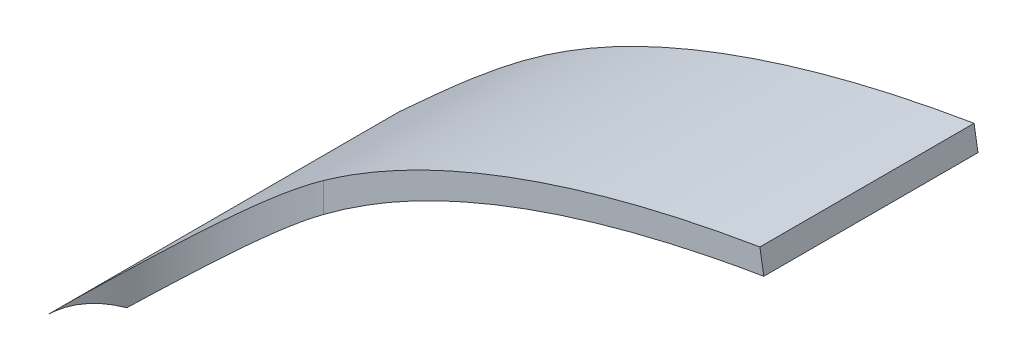
SolidWorks part; units mm, degrees
ref_plane "前视基准面" through (0, 0, 0) normal (0, 0, 1) x (1, 0, 0)
ref_plane "上视基准面" through (0, 0, 0) normal (0, 1, 0) x (1, 0, 0)
ref_plane "右视基准面" through (0, 0, 0) normal (1, 0, 0) x (0, 0, -1)
sketch "草图1" plane through (0, 0, 0) normal (0, 0, 1) x (1, 0, 0)
  line L0 (-29.364, 0) -> (29.364, 0) construction
  line L1 (0, 26.3958) -> (0, -25.1943) construction
  line L2 (-20.4594, 17) -> (13.1095, 17) construction
  line L3 (-20.9541, 10) -> (15.4417, 10) construction
  line L4 (-14.5, 22.6502) -> (-14.5, -16.5724) construction
  line L5 (-14.5, 10) -> (0, 17) construction
  line L6 (0.0993, 16.4083) -> (0, 17)
  line L7 (-14.5, 10) -> (-14.0953, 9.557)
  spline S0 degree 3 poles (-14.5, 10) (-13.2757, 11.1183) (-10.6672, 13.5203) (-5.6205, 15.8092) (-1.9239, 16.6772) (0, 17) knots 0 0 0 0 0.304838 0.643087 1 1 1 1
  spline S1 degree 1 poles (-14.0953, 9.557) (0.0993, 16.4083) knots 0 0 1 1 construction
  spline S2 degree 3 poles (-14.0953, 9.557) (-13.1018, 10.4645) (-11.5913, 11.8562) (-9.4082, 13.3081) (-7.0317, 14.5122) (-3.8568, 15.62) (-1.2248, 16.1861) (0.0993, 16.4083) knots 0 0 0 0 0.25 0.375 0.5 0.75 1 1 1 1
  dimension "D1" = 10
  dimension "D2" = 17
  dimension "D3" = 14.5
  dimension "D4" = 0.6
  dimension "D5" = 0.6
  dimension "D6" = 1.2
  dimension "D7" = 1.2
  dimension "D8" = 0.6
extrude "凸台-拉伸1" add sketch "草图1" along normal blind 10
sketch "草图2" plane through (0, 0, 0) normal (0, 1, 0) x (1, 0, 0)
  line L0 (6.3953, 0) -> (-19.5328, 0) construction
  line L1 (0, 7.2061) -> (0, -15.5323) construction
  line L2 (2.5424, -5.4) -> (-11, -5.4)
  line L3 (-14.5, -10) -> (0, -10) construction
  line L4 (-14.5, -10) -> (-14.5, -8.9)
  line L5 (-14.5, -10) -> (-14.5, 0) construction
  line L6 (2.5424, -5.4) -> (2.5424, -12.2709)
  line L7 (2.5424, -12.2709) -> (-14.5, -12.2709)
  line L8 (-14.5, -12.2709) -> (-14.5, -10)
  arc A0 (-14.5, -8.9) -> (-11, -5.4) centre (-11, -8.9) cw
  dimension "D2" = 3.5
  dimension "D1" = 4.6
extrude "切除-拉伸1" cut sketch "草图2" along normal blind 31
